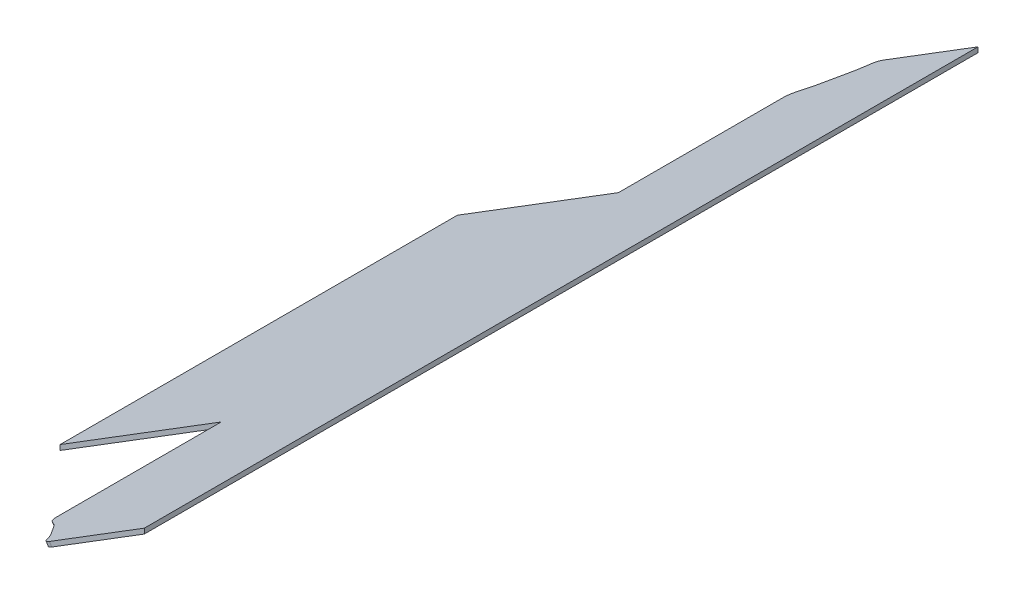
SolidWorks part; units mm, degrees
ref_plane "Front Plane" through (0, 0, 0) normal (0, 0, 1) x (1, 0, 0)
ref_plane "Top Plane" through (0, 0, 0) normal (0, 1, 0) x (1, 0, 0)
ref_plane "Right Plane" through (0, 0, 0) normal (1, 0, 0) x (0, 0, -1)
ref_plane "Plane1" through (184.0612, -296.1905, 0) normal (-0.5278, 0.8494, 0) x (-0.8494, -0.5278, 0)
sketch "Sketch1" plane through (184.0612, -296.1905, 0) normal (-0.5278, 0.8494, 0) x (-0.8494, -0.5278, 0)
  line L0 (-255.9175, -402) -> (-255.9175, -20)
  line L1 (-255.9175, -20) -> (-419.0676, -20)
  line L2 (-419.0676, -20) -> (-419.0676, -402)
  line L3 (-419.0676, -402) -> (-255.9175, -402)
  dimension "D1" = 382
extrude "Boss-Extrude1" add sketch "Sketch1" against normal blind 2
sketch "Sketch2" plane through (185.1169, -297.8892, 0) normal (0.5278, -0.8494, 0) x (0.8494, 0.5278, 0)
  line L0 (255.9175, -120) -> (342.8103, -120)
  line L1 (342.8103, -120) -> (342.8103, 8)
  line L2 (342.8103, 8) -> (255.9175, 8)
  line L3 (255.9175, 8) -> (255.9175, -120)
  line L4 (419.0676, -20) -> (419.0676, -402) construction
  line L5 (255.9175, -20) -> (419.0676, -20) construction
  dimension "D1" = 100
  dimension "D2" = 86.8929
  dimension "D3" = 76.2572
extrude "Cut-Extrude1" cut sketch "Sketch2" against normal through all
sketch "Sketch3" plane through (185.1169, -297.8892, 0) normal (0.5278, -0.8494, 0) x (0.8494, 0.5278, 0)
  line L0 (255.9175, -402) -> (342.8103, -402)
  line L1 (342.8103, -402) -> (342.8103, -302)
  line L2 (342.8103, -302) -> (255.9175, -302)
  line L3 (255.9175, -302) -> (255.9175, -402)
  line L4 (419.0676, -20) -> (419.0676, -402) construction
  line L5 (419.0676, -402) -> (255.9175, -402) construction
  dimension "D1" = 100
  dimension "D2" = 86.8929
  dimension "D3" = 76.2572
extrude "Cut-Extrude2" cut sketch "Sketch3" against normal through all
draft "Draft1" type of draft neutral plane draft angle 31.858 faces to draft 1 face at (540.5278, -75.8494, -211) neutral plane through (184.0612, -296.1905, 0) neutral plane normal (-0.5278, 0.8494, 0) reverse direction yes parameters "D1"=31.858
draft "Draft2" type of draft neutral plane draft angle 31.858 faces to draft 1 face at (401.9548, -161.9626, -211) neutral plane through (184.0612, -296.1905, 0) neutral plane normal (-0.5278, 0.8494, 0) parameters "D1"=31.858
sketch "Sketch4" plane through (185.1169, -297.8892, 0) normal (0.5278, -0.8494, 0) x (0.8494, 0.5278, 0)
  line L0 (342.8103, -20) -> (364.8103, -20)
  line L1 (342.8103, -380) -> (342.8103, -402)
  line L2 (342.8103, -402) -> (364.8103, -402)
  line L3 (342.8103, -42) -> (342.8103, -20)
  line L4 (254.6746, -211) -> (433.0014, -211) construction
  line L5 (254.6746, -302) -> (254.6746, -120) construction
  spline S0 degree 3 poles (342.8103, -42) (346.3027, -39.9428) (351.3007, -36.6607) (356.3503, -31.0608) (361.0893, -26.6967) (363.5659, -22.6944) (364.8103, -20) knots 0 0 0 0 0.388085 0.560148 0.716553 1 1 1 1
  spline S1 degree 3 poles (342.8103, -380) (346.3027, -382.0572) (351.3007, -385.3393) (356.3503, -390.9392) (361.0893, -395.3033) (363.5659, -399.3056) (364.8103, -402) knots 0 0 0 0 0.388085 0.560148 0.716553 1 1 1 1
  dimension "D1" = 22
  dimension "D2" = 22
extrude "Cut-Extrude3" cut sketch "Sketch4" against normal through all
fillet "Fillet1" radius 5 4 edges at (494.444, -104.4872, -20) (475.7581, -116.0991, -42) (494.444, -104.4872, -402) (475.7581, -116.0991, -380)
